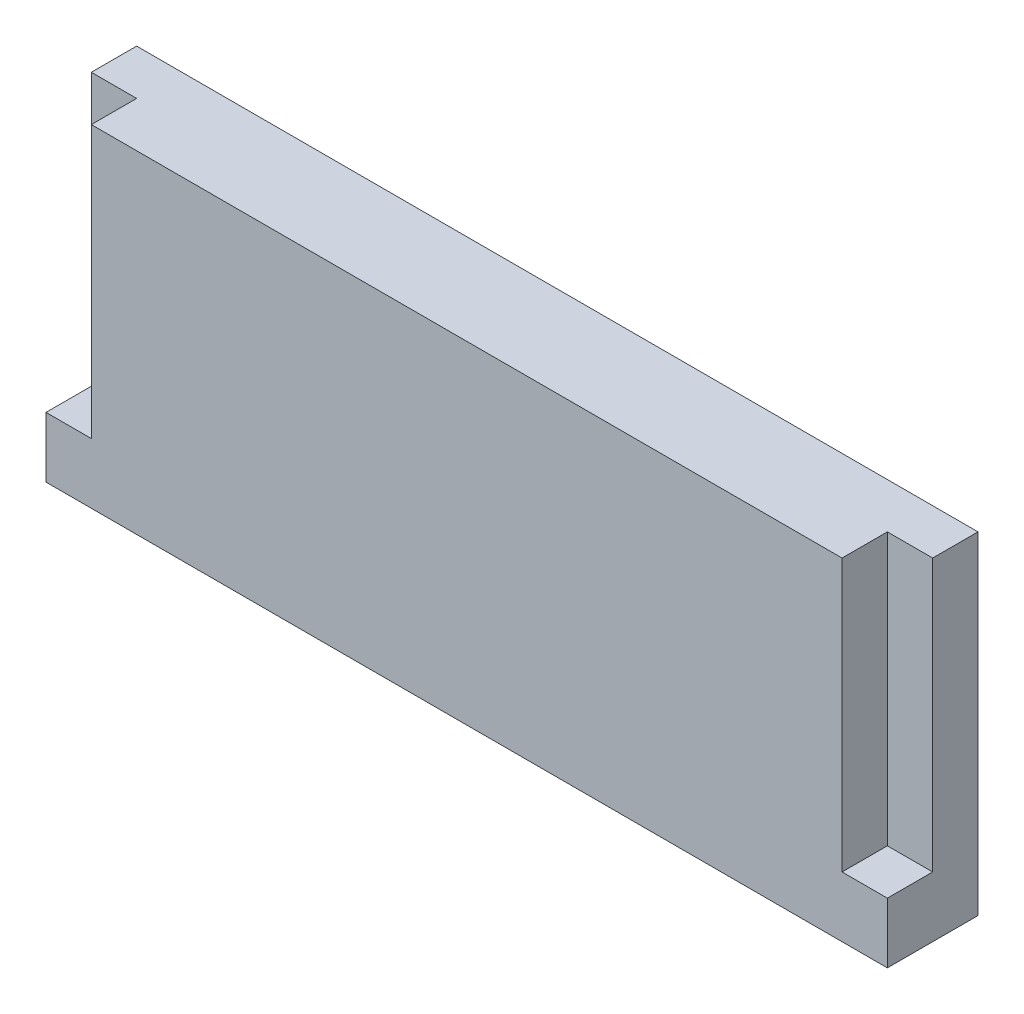
SolidWorks part; units mm, degrees
ref_plane "前视基准面" through (0, 0, 0) normal (0, 0, 1) x (1, 0, 0)
ref_plane "上视基准面" through (0, 0, 0) normal (0, 1, 0) x (1, 0, 0)
ref_plane "右视基准面" through (0, 0, 0) normal (1, 0, 0) x (0, 0, -1)
sketch "草图1" plane through (0, 0, 0) normal (0, 1, 0) x (1, 0, 0)
  line L0 (0, 0) -> (3, 0)
  line L1 (3, 0) -> (3, -3)
  line L2 (3, -3) -> (52.7, -3)
  line L3 (52.7, -3) -> (52.7, 0)
  line L4 (52.7, 0) -> (55.7, 0)
  line L5 (55.7, 0) -> (55.7, 3)
  line L6 (55.7, 3) -> (0, 3)
  line L7 (0, 3) -> (0, 0)
  dimension "D1" = 55.7
  dimension "D2" = 49.7
  dimension "D3" = 3
  dimension "D4" = 3
  dimension "D5" = 3
extrude "凸台-拉伸1" add sketch "草图1" along normal blind 18
sketch "草图2" plane through (0, 0, 0) normal (0, -1, 0) x (1, 0, 0)
  line L0 (55.7, 0) -> (55.7, -3) construction
  line L1 (0, 3) -> (55.7, 3)
  line L2 (0, 3) -> (0, -3)
  line L3 (0, -3) -> (55.7, -3)
  line L4 (55.7, 3) -> (55.7, -3)
  line L5 (0, -3) -> (0, 0) construction
  line L6 (3, 3) -> (52.7, 3) construction
  line L7 (55.7, -3) -> (0, -3) construction
extrude "凸台-拉伸2" add sketch "草图2" along normal blind 4
